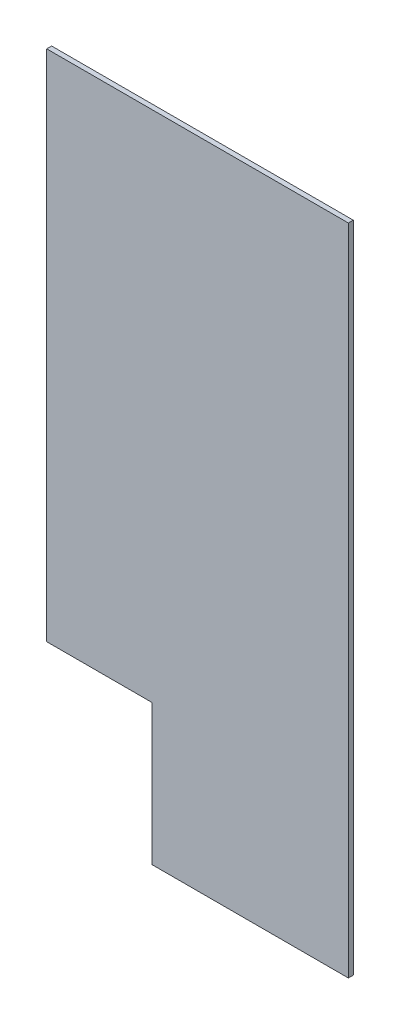
SolidWorks part; units mm, degrees
ref_plane "Спереди" through (0, 0, 0) normal (0, 0, 1) x (1, 0, 0)
ref_plane "Сверху" through (0, 0, 0) normal (0, 1, 0) x (1, 0, 0)
ref_plane "Справа" through (0, 0, 0) normal (1, 0, 0) x (0, 0, -1)
sketch "Эскиз1" plane through (0, 0, 0) normal (0, 1, 0) x (1, 0, 0)
  line L1 (0, 0) -> (245.9852, 0)
  line L2 (0, 0) -> (0, -4)
  line L3 (0, -4) -> (245.9852, -4)
  line L4 (245.9852, 0) -> (245.9852, -4)
extrude "Вытянуть1" add sketch "Эскиз1" along normal up to surface (418.7137 mm away)
sketch "Эскиз2" plane through (0, 0, 0) normal (0, -1, 0) x (1, 0, 0)
  line L0 (245.9852, 0) -> (0, 0) construction
  line L1 (245.9852, 4) -> (85.9852, 4)
  line L2 (245.9852, 4) -> (245.9852, 0)
  line L3 (245.9852, 0) -> (85.9852, 0)
  line L4 (85.9852, 4) -> (85.9852, 0)
extrude "Вытянуть2" add sketch "Эскиз2" along normal up to surface (114.5 mm away)
